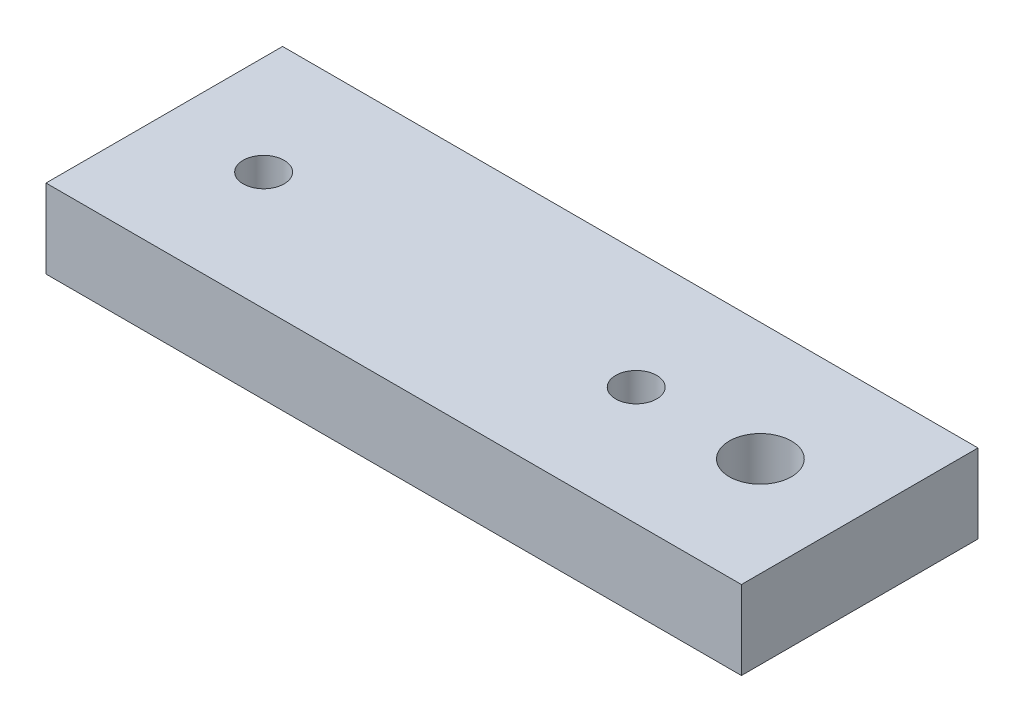
SolidWorks part; units mm, degrees
ref_plane "Front Plane" through (0, 0, 0) normal (0, 0, 1) x (1, 0, 0)
ref_plane "Top Plane" through (0, 0, 0) normal (0, 1, 0) x (1, 0, 0)
ref_plane "Right Plane" through (0, 0, 0) normal (1, 0, 0) x (0, 0, -1)
sketch "Sketch1" plane through (0, 0, 0) normal (0, 1, 0) x (1, 0, 0)
  line L1 (28, -9.525) -> (-28, -9.525)
  line L2 (28, -9.525) -> (28, 9.525)
  line L3 (28, 9.525) -> (-28, 9.525)
  line L4 (-28, -9.525) -> (-28, 9.525)
  line L5 (28, -9.525) -> (-28, 9.525) construction
  line L6 (28, 9.525) -> (-28, -9.525) construction
  point P0 (0, 0)
  dimension "D1" = 19.05
  dimension "D2" = 56
extrude "Boss-Extrude1" add sketch "Sketch1" along normal blind 6.35
sketch "Sketch2" plane through (0, 6.35, 0) normal (0, 1, 0) x (1, 0, 0)
  line L0 (-20, 0) -> (20, 0) construction
  line L1 (-28, 9.525) -> (-28, -9.525) construction
  point P5 (21, 0)
  dimension "D1" = 8
hole_wizard "M6x1.0 Tapped Hole1" positions "3DSketch1" profile "Sketch3" tap size "M6x1.0" standard "ANSI Metric" end condition through all
sketch3d "3DSketch1"
  point P3 (20, 6.35, 0)
sketch "Sketch3" plane through (20, 6.35, 0) normal (1, 0, 0) x (0, 0, 1)
  line L0 (0, 0) -> (0, 6.35)
  line L1 (0, 6.35) -> (2.5, 6.35)
  line L2 (2.5, 6.35) -> (2.5, 0)
  line L5 (2.5, 0) -> (0, 0)
  line L11 (0, -6.35) -> (0, 107.95) construction
  dimension "Thru Tap Drill Dia." = 5
  dimension "Thru Tap Drill Depth" = 6.35
cosmetic thread "Hole Thread1" parameters "D2"=6
sketch "Sketch4" plane through (0, 6.35, 0) normal (0, 1, 0) x (1, 0, 0)
  line L0 (-28, 0) -> (28, 0) construction
  line L1 (-28, 9.525) -> (-28, -9.525) construction
  line L2 (28, -9.525) -> (28, 9.525) construction
  point P0 (-20, 0)
  point P1 (10, 0)
  dimension "D1" = 30
  dimension "D2" = 8
hole_wizard "M4x0.7 Tapped Hole1" positions "3DSketch2" profile "Sketch5" tap size "M4x0.7" standard "BSI" end condition through all
sketch3d "3DSketch2"
  point P0 (-20, 6.35, 0)
  point P3 (10, 6.35, 0)
sketch "Sketch5" plane through (-20, 6.35, 0) normal (1, 0, 0) x (0, 0, 1)
  line L0 (0, 0) -> (0, 6.35)
  line L1 (0, 6.35) -> (1.65, 6.35)
  line L2 (1.65, 6.35) -> (1.65, 0)
  line L5 (1.65, 0) -> (0, 0)
  line L11 (0, -6.35) -> (0, 107.95) construction
  dimension "Thru Tap Drill Dia." = 3.3
  dimension "Thru Tap Drill Depth" = 6.35
cosmetic thread "Hole Thread2" parameters "D2"=4
cosmetic thread "Hole Thread3" parameters "D2"=4
